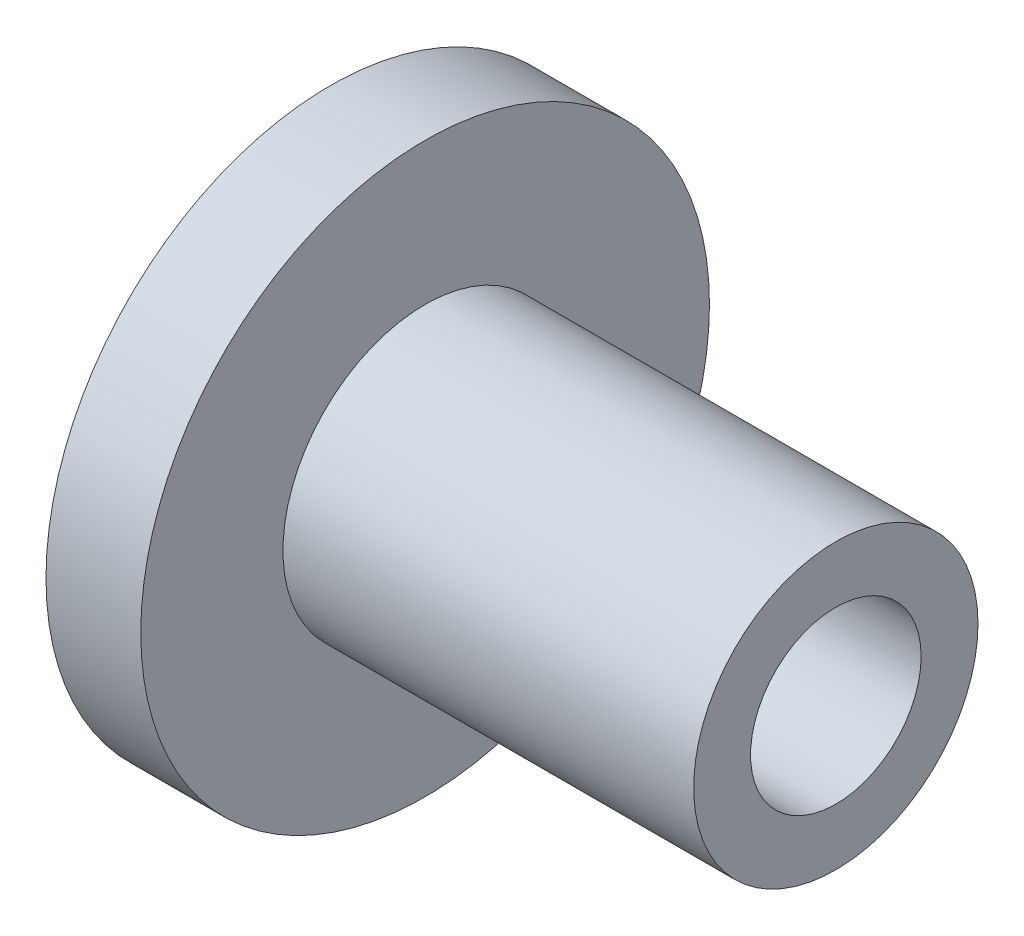
SolidWorks part; units mm, degrees
ref_plane "Спереди" through (0, 0, 0) normal (0, 0, 1) x (1, 0, 0)
ref_plane "Сверху" through (0, 0, 0) normal (0, 1, 0) x (1, 0, 0)
ref_plane "Справа" through (0, 0, 0) normal (1, 0, 0) x (0, 0, -1)
sketch "Эскиз1" plane through (0, 0, 0) normal (0, 0, 1) x (1, 0, 0)
  line L0 (0, 0) -> (-34.5542, 0) construction
  line L1 (0, 1.35) -> (0, 4.5)
  line L2 (0, 4.5) -> (1.5, 4.5)
  line L3 (1.5, 4.5) -> (1.5, 2.25)
  line L4 (1.5, 2.25) -> (8, 2.25)
  line L5 (8, 2.25) -> (8, 1.35)
  line L6 (8, 1.35) -> (0, 1.35)
  line L7 (0, 1.35) -> (0, 0) construction
  dimension "D1" = 2.7
  dimension "D2" = 4.5
  dimension "D3" = 9
  dimension "D4" = 1.5
  dimension "D5" = 6.5
revolve "Повернуть1" add sketch "Эскиз1" angle 360 about L0
